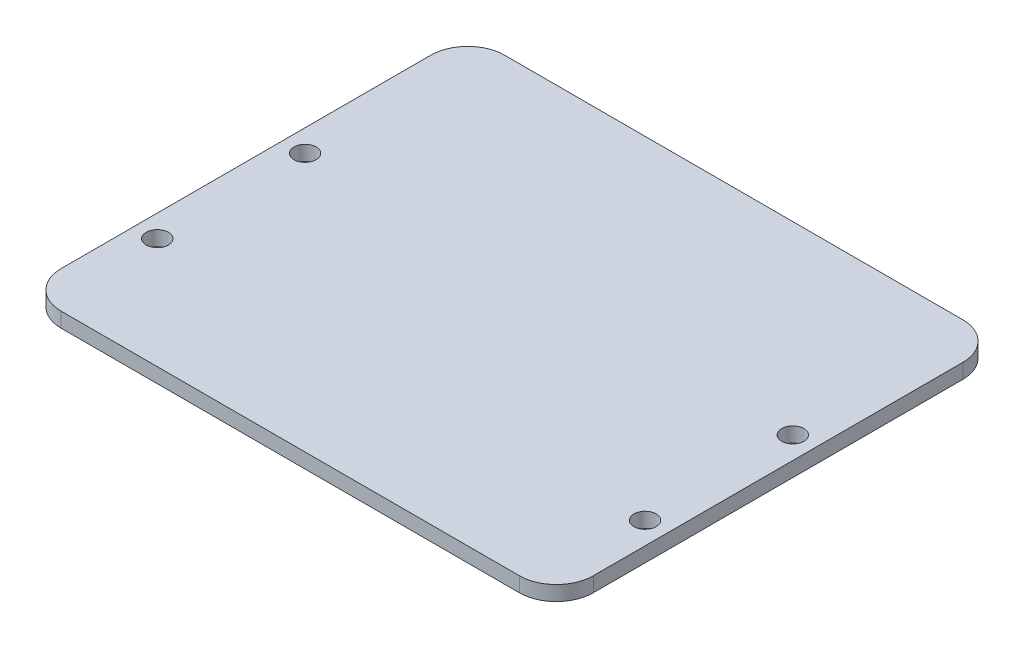
SolidWorks part; units mm, degrees
material "有机玻璃 (TM) GS 丙烯酸铸钣"
ref_plane "前视基准面" through (0, 0, 0) normal (0, 0, 1) x (1, 0, 0)
ref_plane "上视基准面" through (0, 0, 0) normal (0, 1, 0) x (1, 0, 0)
ref_plane "右视基准面" through (0, 0, 0) normal (1, 0, 0) x (0, 0, -1)
other "Configuration Table"
sketch "草图1" plane through (0, 0, 0) normal (0, 1, 0) x (1, 0, 0)
  line L0 (-33, 5) -> (-33, -15) construction
  line L1 (-36, 30) -> (36, 30)
  line L2 (-36, 30) -> (-36, -30)
  line L3 (-36, -30) -> (36, -30)
  line L4 (36, 30) -> (36, -30)
  line L5 (-36, 30) -> (36, -30) construction
  line L6 (-36, -30) -> (36, 30) construction
  line L7 (0, 0) -> (0, -30) construction
  line L8 (-36, -20) -> (36, -20) construction
  circle A0 centre (-33, 5) radius 1.5
  circle A1 centre (-33, -15) radius 1.5
  circle A2 centre (33, -15) radius 1.5
  circle A3 centre (33, 5) radius 1.5
  point P0 (0, 0)
  dimension "D5" = 3
  dimension "D1" = 60
  dimension "D2" = 20
  dimension "D3" = 20
  dimension "D4" = 3
  dimension "D6" = 72
  dimension "D7" = 5
extrude "凸台-拉伸1" add sketch "草图1" along normal blind 2
fillet "圆角1" radius 5 4 edges at (36, 1, 30) (-36, 1, -30) (36, 1, -30) (-36, 1, 30)
